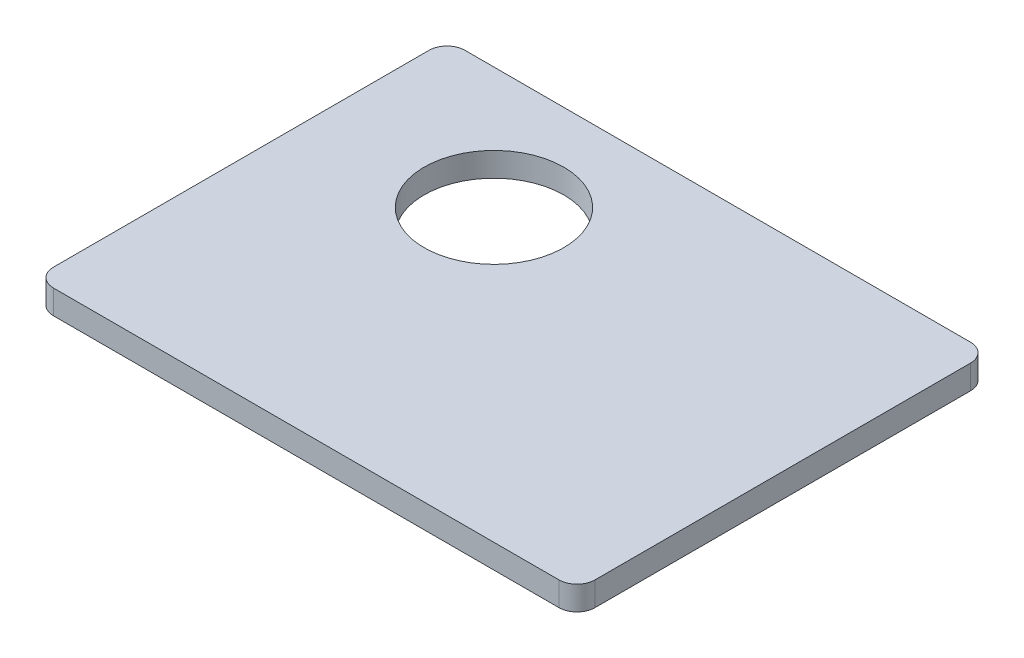
SolidWorks part; units mm, degrees
ref_plane "Спереди" through (0, 0, 0) normal (0, 0, 1) x (1, 0, 0)
ref_plane "Сверху" through (0, 0, 0) normal (0, 1, 0) x (1, 0, 0)
ref_plane "Справа" through (0, 0, 0) normal (1, 0, 0) x (0, 0, -1)
sketch "Эскиз1" plane through (0, 0, 0) normal (0, 1, 0) x (1, 0, 0)
  line L0 (-11.7596, -6.9079) -> (11.2404, -24.5079) construction
  line L1 (-10.7596, -6.9079) -> (10.2404, -6.9079)
  line L2 (-11.7596, -7.9079) -> (-11.7596, -23.5079) construction
  line L3 (-10.7596, -24.5079) -> (10.2404, -24.5079)
  line L4 (11.2404, -7.9079) -> (11.2404, -23.5079)
  line L5 (-10.7596, -7.1579) -> (10.2404, -7.1579)
  line L6 (10.9904, -7.9079) -> (10.9904, -23.5079)
  line L7 (-10.7596, -24.2579) -> (10.2404, -24.2579)
  line L8 (-11.5096, -7.9079) -> (-11.5096, -23.5079)
  arc A0 (-11.7596, -23.5079) -> (-10.7596, -24.5079) centre (-10.7596, -23.5079) ccw
  arc A1 (10.2404, -24.5079) -> (11.2404, -23.5079) centre (10.2404, -23.5079) ccw
  arc A2 (10.2404, -6.9079) -> (11.2404, -7.9079) centre (10.2404, -7.9079) cw
  arc A3 (-10.7596, -6.9079) -> (-11.7596, -7.9079) centre (-10.7596, -7.9079) ccw
  arc A4 (10.2404, -7.1579) -> (10.9904, -7.9079) centre (10.2404, -7.9079) cw
  arc A5 (10.2404, -24.2579) -> (10.9904, -23.5079) centre (10.2404, -23.5079) ccw
  arc A6 (-11.5096, -23.5079) -> (-10.7596, -24.2579) centre (-10.7596, -23.5079) ccw
  arc A7 (-10.7596, -7.1579) -> (-11.5096, -7.9079) centre (-10.7596, -7.9079) ccw
  dimension "D1" = 1
  dimension "D2" = 0.25
extrude "Бобышка-Вытянуть1" add sketch "Эскиз1" along normal blind 1 contours L5 A7 L8 A6 L7 A5 L6 A4
sketch "Эскиз2" plane through (0, 1, 0) normal (0, 1, 0) x (1, 0, 0)
  line L0 (-0.2596, -7.1579) -> (-0.2596, -24.2579) construction
  line L1 (-10.7596, -7.1579) -> (10.2404, -7.1579) construction
  line L2 (-10.7596, -24.2579) -> (10.2404, -24.2579) construction
  line L3 (-12.1738, -6.4937) -> (11.6546, -24.9221) construction
  line L4 (-12.1738, -24.9221) -> (11.6546, -6.4937) construction
  circle A0 centre (3.9904, -12.2079) radius 2.9 construction
  circle A1 centre (-4.5096, -12.2079) radius 2.9
extrude "Вырез-Вытянуть1" cut sketch "Эскиз2" against normal blind 1
